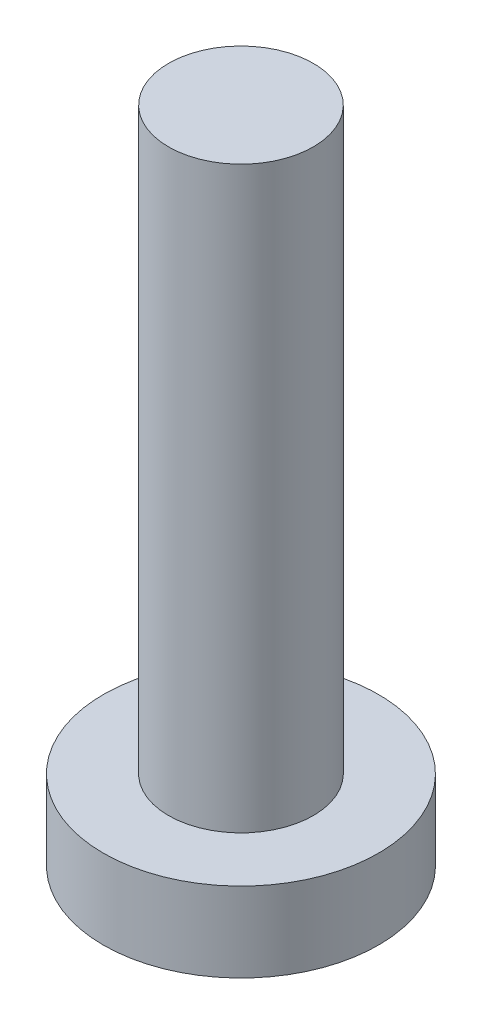
SolidWorks part; units mm, degrees
ref_plane "前视基准面" through (0, 0, 0) normal (0, 0, 1) x (1, 0, 0)
ref_plane "上视基准面" through (0, 0, 0) normal (0, 1, 0) x (1, 0, 0)
ref_plane "右视基准面" through (0, 0, 0) normal (1, 0, 0) x (0, 0, -1)
sketch "草图1" plane through (0, 0, 0) normal (0, 1, 0) x (1, 0, 0)
  circle A0 centre (0, 0) radius 2.85
  dimension "D1" = 5.7
extrude "凸台-拉伸1" add sketch "草图1" along normal blind 1.65
sketch "草图2" plane through (0, 1.65, 0) normal (0, 1, 0) x (1, 0, 0)
  circle A0 centre (0, 0) radius 1.5
  dimension "D1" = 3
extrude "凸台-拉伸2" add sketch "草图2" along normal blind 12
